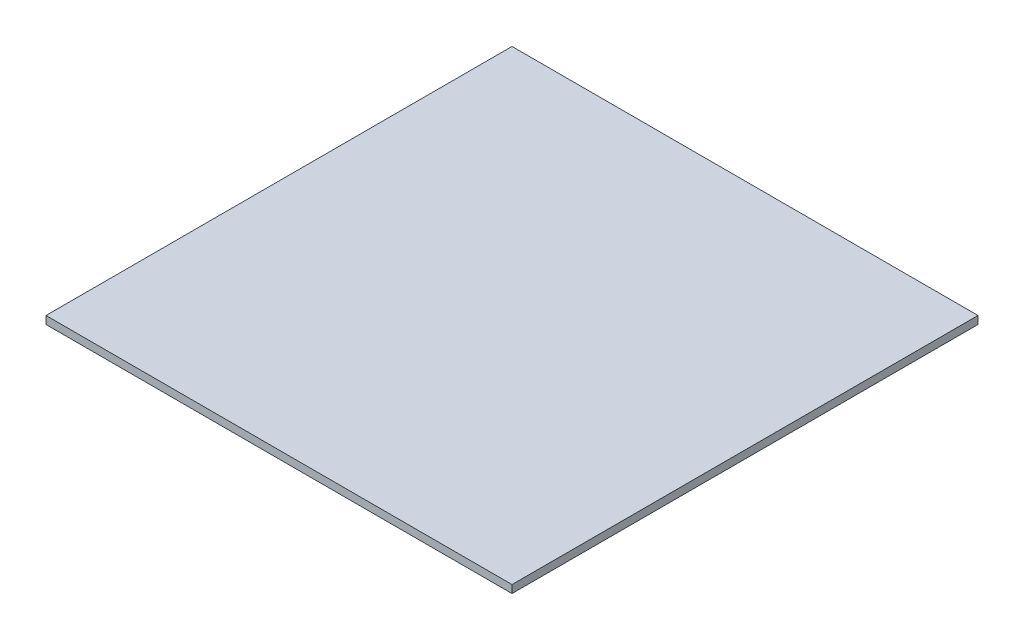
SolidWorks part; units mm, degrees
ref_plane "Front Plane" through (0, 0, 0) normal (0, 0, 1) x (1, 0, 0)
ref_plane "Top Plane" through (0, 0, 0) normal (0, 1, 0) x (1, 0, 0)
ref_plane "Right Plane" through (0, 0, 0) normal (1, 0, 0) x (0, 0, -1)
sketch "Sketch1" plane through (0, 0, 0) normal (0, 1, 0) x (1, 0, 0)
  line L1 (-297.5, -297.5) -> (297.5, -297.5)
  line L2 (-297.5, -297.5) -> (-297.5, 297.5)
  line L3 (-297.5, 297.5) -> (297.5, 297.5)
  line L4 (297.5, -297.5) -> (297.5, 297.5)
  line L5 (-297.5, -297.5) -> (297.5, 297.5) construction
  line L6 (-297.5, 297.5) -> (297.5, -297.5) construction
  point P0 (0, 0)
  dimension "D1" = 595
extrude "Boss-Extrude1" add sketch "Sketch1" along normal blind 10
